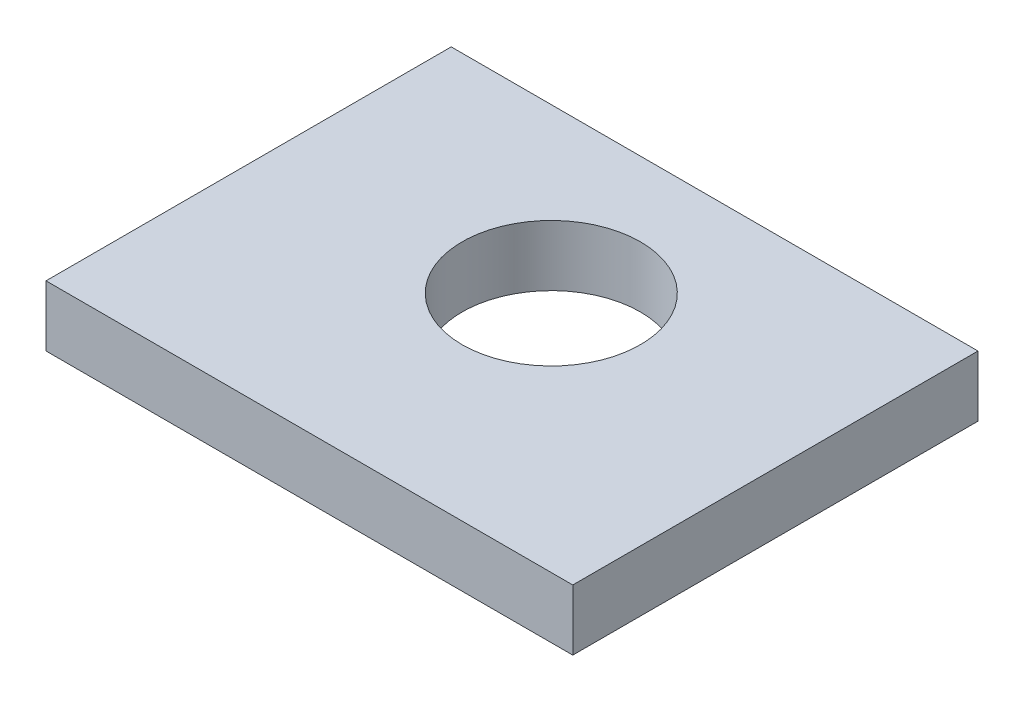
SolidWorks part; units mm, degrees
ref_plane "Front Plane" through (0, 0, 0) normal (0, 0, 1) x (1, 0, 0)
ref_plane "Top Plane" through (0, 0, 0) normal (0, 1, 0) x (1, 0, 0)
ref_plane "Right Plane" through (0, 0, 0) normal (1, 0, 0) x (0, 0, -1)
sketch "Sketch1" plane through (0, 0, 0) normal (0, 1, 0) x (1, 0, 0)
  line L1 (-3.25, -2.5) -> (3.25, -2.5)
  line L2 (-3.25, -2.5) -> (-3.25, 2.5)
  line L3 (-3.25, 2.5) -> (3.25, 2.5)
  line L4 (3.25, -2.5) -> (3.25, 2.5)
  line L5 (-3.25, -2.5) -> (3.25, 2.5) construction
  line L6 (-3.25, 2.5) -> (3.25, -2.5) construction
  point P0 (0, 0)
  dimension "D1" = 6.5
  dimension "D2" = 5
extrude "Boss-Extrude1" add sketch "Sketch1" along normal blind 0.75
sketch "Sketch2" plane through (0, 0, 0) normal (0, 1, 0) x (1, 0, 0)
  circle A0 centre (0, 0.4847) radius 2.653 construction
  circle A1 centre (0, 0.4847) radius 2.653 construction
  circle A2 centre (0, 0.4847) radius 1.1
  dimension "D1" = 2.2
extrude "Cut-Extrude1" cut sketch "Sketch2" along normal through all
